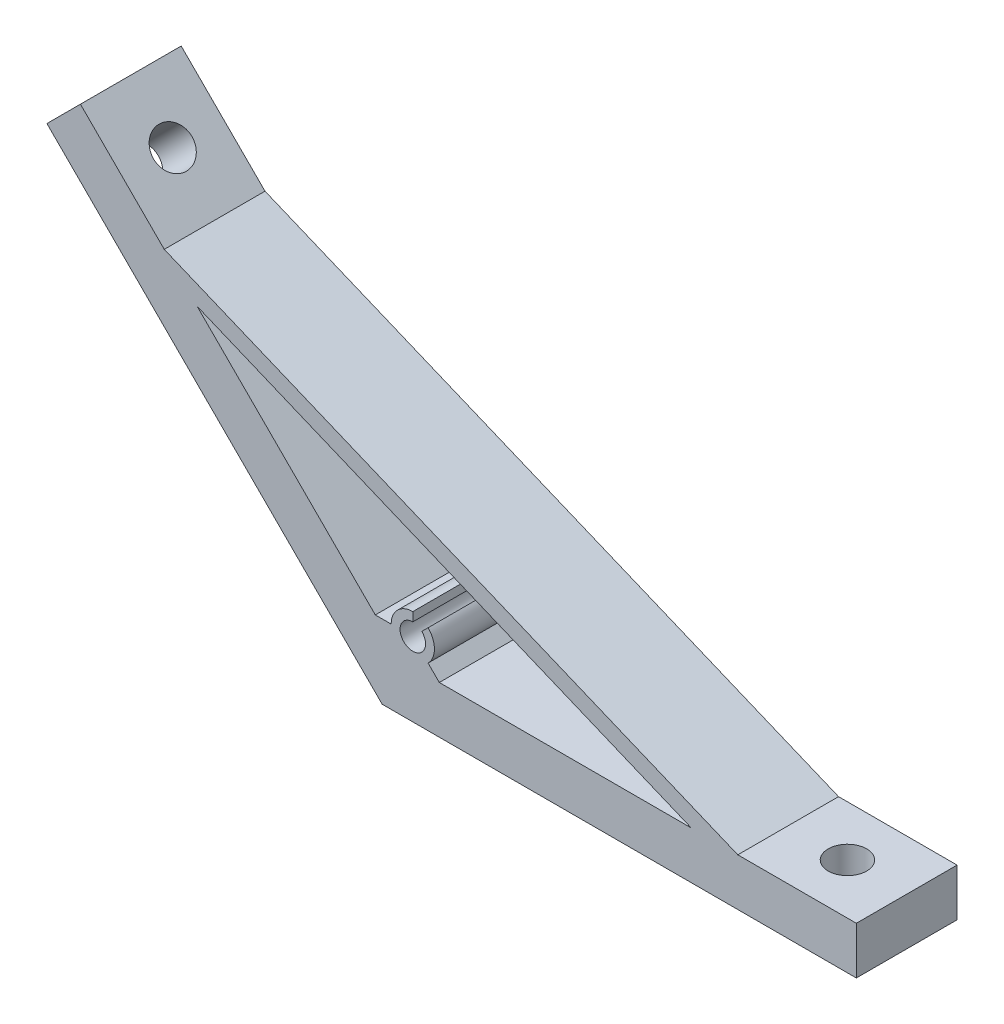
SolidWorks part; units mm, degrees
ref_plane "前视基准面" through (0, 0, 0) normal (0, 0, 1) x (1, 0, 0)
ref_plane "上视基准面" through (0, 0, 0) normal (0, 1, 0) x (1, 0, 0)
ref_plane "右视基准面" through (0, 0, 0) normal (1, 0, 0) x (0, 0, -1)
sketch "草图1" plane through (0, 0, 0) normal (0, 0, 1) x (1, 0, 0)
  line B0 (80, 0) -> (0, 0)
  line B1 (80, 8) -> (60, 8)
  line B2 (52.1606, 8) -> (9.6386, 8)
  line B3 (0, 0) -> (-56.5685, 56.5685)
  line B4 (-1.1587, 12.4724) -> (-31.2263, 42.54)
  line B5 (-36.7696, 48.0833) -> (-50.9117, 62.2254)
  line B6 (-50.9117, 62.2254) -> (-56.5685, 56.5685)
  line B7 (80, 8) -> (80, 0)
  line B8 (-1.1587, 12.4724) -> (1.5162, 12.4724)
  line B9 (9.6386, 8) -> (7.7472, 9.8914)
  line B10 (6.6865, 13.9927) -> (7.7472, 15.0533)
  line B11 (5.1662, 14.6224) -> (5.1662, 16.1224)
  line B12 (-36.7696, 48.0833) -> (60, 8)
  line B13 (-31.2263, 42.54) -> (52.1606, 8)
  arc B14 (5.1662, 14.6224) -> (6.6865, 13.9927) centre (5.1662, 12.4724) ccw
  arc B15 (7.7472, 9.8914) -> (7.7472, 15.0533) centre (5.1662, 12.4724) ccw
  arc B16 (5.1662, 16.1224) -> (1.5162, 12.4724) centre (5.1662, 12.4724) ccw
sketch_block_instance "A$C053212F5-1"
sketch_block "A$C053212F5"
extrude "凸台-拉伸1" add sketch "草图1" along normal mid plane 17
sketch "草图3" plane through (0, 8, 0) normal (0, 1, 0) x (1, 0, 0)
  line L0 (80, -8.5) -> (80, 8.5) construction
  circle A0 centre (70, 0) radius 3.25
  dimension "D1" = 10
extrude "切除-拉伸1" cut sketch "草图3" against normal through all
sketch "草图4" plane through (11.6152, 28.0416, 0) normal (0.3827, 0.9239, 0) x (0.9239, -0.3827, 0)
  line L0 (0, -8.5) -> (0, 8.5) construction
  line L1 (52.3713, -8.5) -> (-52.3713, -8.5) construction
  line L2 (52.3713, 8.5) -> (-52.3713, 8.5) construction
ref_plane "基准面2" through (0, 0, 0) normal (-0.9239, 0.3827, 0) x (0, 0, 1)
mirror "镜向1" about plane through (0, 0, 0) normal (-0.9239, 0.3827, 0) of "切除-拉伸1"
